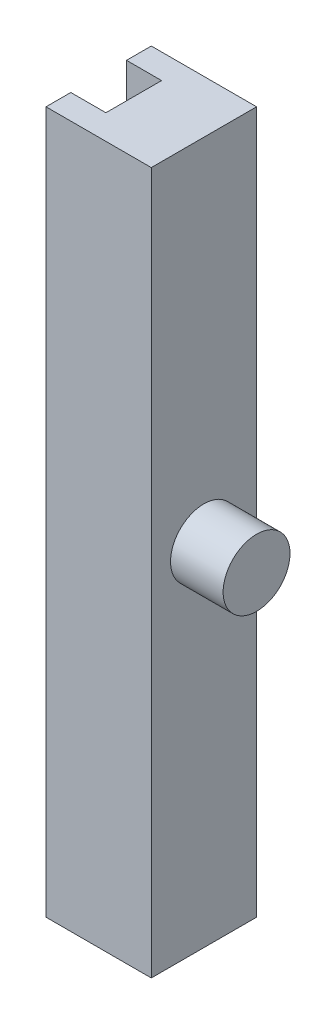
SolidWorks part; units mm, degrees
material "ABS"
ref_plane "Front Plane" through (0, 0, 0) normal (0, 0, 1) x (1, 0, 0)
ref_plane "Top Plane" through (0, 0, 0) normal (0, 1, 0) x (1, 0, 0)
ref_plane "Right Plane" through (0, 0, 0) normal (1, 0, 0) x (0, 0, -1)
sketch "Sketch2" plane through (0, 0, 0) normal (0, 1, 0) x (1, 0, 0)
  line L0 (0, 0) -> (6, 0)
  line L1 (6, 0) -> (6, 6)
  line L2 (6, 6) -> (0, 6)
  line L3 (0, 6) -> (0, 4.5875)
  line L4 (0, 4.5875) -> (2, 4.5875)
  line L5 (2, 4.5875) -> (2, 1.4125)
  line L6 (2, 1.4125) -> (0, 1.4125)
  line L7 (0, 1.4125) -> (0, 0)
  point P3 (2, 3)
  point P10 (6, 3)
  dimension "D1" = 6
  dimension "D2" = 3.175
  dimension "D3" = 6
  dimension "D4" = 2
extrude "Boss-Extrude1" add sketch "Sketch2" against normal blind 40
sketch "Sketch3" plane through (6, 0, 0) normal (1, 0, 0) x (0, 0, -1)
  line L0 (3, 0) -> (3, -40) construction
  line L1 (0, 0) -> (6, 0) construction
  line L2 (0, -40) -> (6, -40) construction
  circle A0 centre (3, -20) radius 1.905
  dimension "D1" = 3.81
extrude "Boss-Extrude2" add sketch "Sketch3" along normal blind 3
